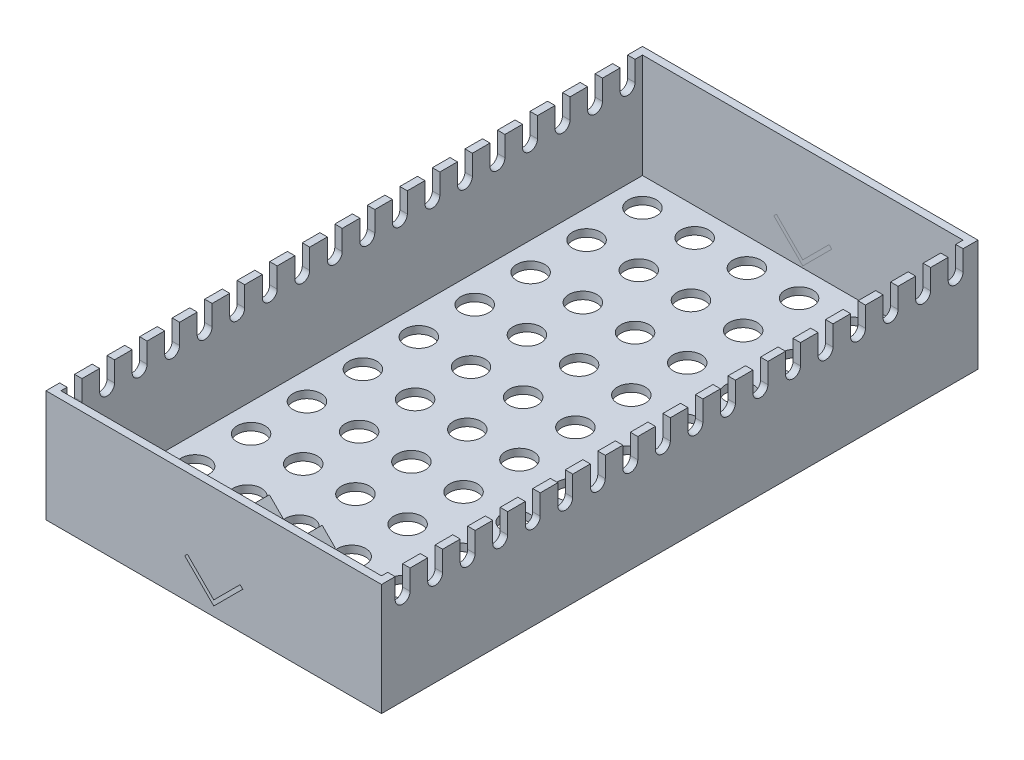
SolidWorks part; units mm, degrees
ref_plane "Front Plane" through (0, 0, 0) normal (0, 0, 1) x (1, 0, 0)
ref_plane "Top Plane" through (0, 0, 0) normal (0, 1, 0) x (1, 0, 0)
ref_plane "Right Plane" through (0, 0, 0) normal (1, 0, 0) x (0, 0, -1)
sketch "Sketch1" plane through (0, 0, 0) normal (0, 0, 1) x (1, 0, 0)
  line L0 (0, 4.9711) -> (-8.9803, 13.9513)
  line L1 (-57.15, 0) -> (57.15, 0)
  line L2 (-57.15, 0) -> (-57.15, 38.1)
  line L3 (-57.15, 38.1) -> (57.15, 38.1)
  line L4 (57.15, 0) -> (57.15, 38.1)
  line L5 (-8.9803, 13.9513) -> (-9.8783, 13.0533)
  line L6 (-9.8783, 13.0533) -> (0, 3.175)
  line L7 (0, 3.175) -> (9.8783, 13.0533)
  line L8 (9.8783, 13.0533) -> (8.9803, 13.9513)
  line L9 (8.9803, 13.9513) -> (0, 4.9711)
  point P10 (0, 0)
  point P12 (0, 0)
  point P13 (0, 0)
  point P14 (9.8783, 13.0533)
  point P15 (0, 0)
  dimension "D1" = 12.7
  dimension "D2" = 1.27
  dimension "D3" = 3.175
  dimension "D4" = 45
  dimension "D5" = 114.3
  dimension "D6" = 38.1
extrude "Boss-Extrude1" add sketch "Sketch1" against normal blind 203.2
shell "Shell1" thickness 2.54
sketch "Sketch3" plane through (0, 0, 0) normal (1, 0, 0) x (0, 0, -1)
  line L0 (203.2, 38.1) -> (0, 38.1) construction
  line L1 (200.66, 38.1) -> (27.94, 38.1)
  line L2 (200.66, 38.1) -> (200.66, 2.54)
  line L3 (200.66, 2.54) -> (27.94, 2.54)
  line L4 (27.94, 38.1) -> (27.94, 2.54)
  line L5 (203.2, 0) -> (0, 0) construction
  line L6 (0, 0) -> (0, 38.1) construction
  line L7 (203.2, 0) -> (203.2, 38.1) construction
  dimension "D1" = 2.54
  dimension "D2" = 27.94
  dimension "D3" = 2.54
extrude "Cut-Extrude1" cut sketch "Sketch3" against normal up to next and the other way up to next
sketch "Sketch4" plane through (0, 0, -27.94) normal (0, 0, -1) x (-1, 0, 0)
  line L5 (-9.8783, 13.0533) -> (-8.9803, 13.9513)
  line L6 (-8.9803, 13.9513) -> (0, 4.9711)
  line L7 (0, 4.9711) -> (8.9803, 13.9513)
  line L8 (8.9803, 13.9513) -> (9.8783, 13.0533)
  line L9 (9.8783, 13.0533) -> (0, 3.175)
  line L10 (0, 3.175) -> (-9.8783, 13.0533)
extrude "Boss-Extrude2" add sketch "Sketch4" against normal blind 2.54
sketch "Sketch5" plane through (-57.15, 0, 0) normal (-1, 0, 0) x (0, 0, 1)
  line L0 (-203.2, 38.1) -> (0, 38.1) construction
  line L1 (-198.12, 38.1) -> (-193.04, 38.1)
  line L2 (-198.12, 38.1) -> (-198.12, 31.242)
  line L4 (-193.04, 38.1) -> (-193.04, 31.242)
  line L5 (-203.2, 38.1) -> (-203.2, 0) construction
  line L6 (-181.958, 38.1) -> (-181.958, 31.242)
  line L7 (-187.038, 38.1) -> (-181.958, 38.1)
  line L8 (-187.038, 38.1) -> (-187.038, 31.242)
  line L9 (-170.876, 38.1) -> (-170.876, 31.242)
  line L10 (-175.956, 38.1) -> (-170.876, 38.1)
  line L11 (-175.956, 38.1) -> (-175.956, 31.242)
  line L12 (-159.794, 38.1) -> (-159.794, 31.242)
  line L13 (-164.874, 38.1) -> (-159.794, 38.1)
  line L14 (-164.874, 38.1) -> (-164.874, 31.242)
  line L15 (-148.7119, 38.1) -> (-148.7119, 31.242)
  line L16 (-153.7919, 38.1) -> (-148.7119, 38.1)
  line L17 (-153.7919, 38.1) -> (-153.7919, 31.242)
  line L18 (-137.6299, 38.1) -> (-137.6299, 31.242)
  line L19 (-142.7099, 38.1) -> (-137.6299, 38.1)
  line L20 (-142.7099, 38.1) -> (-142.7099, 31.242)
  line L21 (-126.5479, 38.1) -> (-126.5479, 31.242)
  line L22 (-131.6279, 38.1) -> (-126.5479, 38.1)
  line L23 (-131.6279, 38.1) -> (-131.6279, 31.242)
  line L24 (-115.4659, 38.1) -> (-115.4659, 31.242)
  line L25 (-120.5459, 38.1) -> (-115.4659, 38.1)
  line L26 (-120.5459, 38.1) -> (-120.5459, 31.242)
  line L27 (-104.3839, 38.1) -> (-104.3839, 31.242)
  line L28 (-109.4639, 38.1) -> (-104.3839, 38.1)
  line L29 (-109.4639, 38.1) -> (-109.4639, 31.242)
  line L30 (-93.3019, 38.1) -> (-93.3019, 31.242)
  line L31 (-98.3819, 38.1) -> (-93.3019, 38.1)
  line L32 (-98.3819, 38.1) -> (-98.3819, 31.242)
  line L33 (-82.2199, 38.1) -> (-82.2199, 31.242)
  line L34 (-87.2999, 38.1) -> (-82.2199, 38.1)
  line L35 (-87.2999, 38.1) -> (-87.2999, 31.242)
  line L36 (-71.1378, 38.1) -> (-71.1378, 31.242)
  line L37 (-76.2178, 38.1) -> (-71.1378, 38.1)
  line L38 (-76.2178, 38.1) -> (-76.2178, 31.242)
  line L39 (-60.0558, 38.1) -> (-60.0558, 31.242)
  line L40 (-65.1358, 38.1) -> (-60.0558, 38.1)
  line L41 (-65.1358, 38.1) -> (-65.1358, 31.242)
  line L42 (-48.9738, 38.1) -> (-48.9738, 31.242)
  line L43 (-54.0538, 38.1) -> (-48.9738, 38.1)
  line L44 (-54.0538, 38.1) -> (-54.0538, 31.242)
  line L45 (-37.8918, 38.1) -> (-37.8918, 31.242)
  line L46 (-42.9718, 38.1) -> (-37.8918, 38.1)
  line L47 (-42.9718, 38.1) -> (-42.9718, 31.242)
  line L48 (-26.8098, 38.1) -> (-26.8098, 31.242)
  line L49 (-31.8898, 38.1) -> (-26.8098, 38.1)
  line L50 (-31.8898, 38.1) -> (-31.8898, 31.242)
  line L51 (-15.7278, 38.1) -> (-15.7278, 31.242)
  line L52 (-20.8078, 38.1) -> (-15.7278, 38.1)
  line L53 (-20.8078, 38.1) -> (-20.8078, 31.242)
  line L54 (-4.6458, 38.1) -> (-4.6458, 31.242)
  line L55 (-9.7258, 38.1) -> (-4.6458, 38.1)
  line L56 (-9.7258, 38.1) -> (-9.7258, 31.242)
  arc A0 (-198.12, 31.242) -> (-193.04, 31.242) centre (-195.58, 31.242) ccw
  arc A1 (-187.038, 31.242) -> (-181.958, 31.242) centre (-184.498, 31.242) ccw
  arc A2 (-175.956, 31.242) -> (-170.876, 31.242) centre (-173.416, 31.242) ccw
  arc A3 (-164.874, 31.242) -> (-159.794, 31.242) centre (-162.334, 31.242) ccw
  arc A4 (-153.7919, 31.242) -> (-148.7119, 31.242) centre (-151.2519, 31.242) ccw
  arc A5 (-142.7099, 31.242) -> (-137.6299, 31.242) centre (-140.1699, 31.242) ccw
  arc A6 (-131.6279, 31.242) -> (-126.5479, 31.242) centre (-129.0879, 31.242) ccw
  arc A7 (-120.5459, 31.242) -> (-115.4659, 31.242) centre (-118.0059, 31.242) ccw
  arc A8 (-109.4639, 31.242) -> (-104.3839, 31.242) centre (-106.9239, 31.242) ccw
  arc A9 (-98.3819, 31.242) -> (-93.3019, 31.242) centre (-95.8419, 31.242) ccw
  arc A10 (-87.2999, 31.242) -> (-82.2199, 31.242) centre (-84.7599, 31.242) ccw
  arc A11 (-76.2178, 31.242) -> (-71.1378, 31.242) centre (-73.6778, 31.242) ccw
  arc A12 (-65.1358, 31.242) -> (-60.0558, 31.242) centre (-62.5958, 31.242) ccw
  arc A13 (-54.0538, 31.242) -> (-48.9738, 31.242) centre (-51.5138, 31.242) ccw
  arc A14 (-42.9718, 31.242) -> (-37.8918, 31.242) centre (-40.4318, 31.242) ccw
  arc A15 (-31.8898, 31.242) -> (-26.8098, 31.242) centre (-29.3498, 31.242) ccw
  arc A16 (-20.8078, 31.242) -> (-15.7278, 31.242) centre (-18.2678, 31.242) ccw
  arc A17 (-9.7258, 31.242) -> (-4.6458, 31.242) centre (-7.1858, 31.242) ccw
  point P9 (-195.58, 28.702)
  dimension "D1" = 5.08
  dimension "D2" = 5.08
  dimension "D3" = 9.398
  dimension "D4" = 18
extrude "Cut-Extrude2" cut sketch "Sketch5" against normal through all both and the other way through all
sketch "Sketch6" plane through (0, 2.54, 0) normal (0, 1, 0) x (1, 0, 0)
  line L0 (54.61, 200.66) -> (-54.61, 200.66) construction
  line L1 (-54.61, 200.66) -> (-54.61, 2.54) construction
  circle A0 centre (-45.085, 191.135) radius 4.7625
  circle A1 centre (-27.305, 191.135) radius 4.7625
  circle A2 centre (-9.525, 191.135) radius 4.7625
  circle A3 centre (8.255, 191.135) radius 4.7625
  circle A4 centre (26.035, 191.135) radius 4.7625
  circle A5 centre (43.815, 191.135) radius 4.7625
  circle A6 centre (-27.305, 172.085) radius 4.7625
  circle A7 centre (-9.525, 172.085) radius 4.7625
  circle A8 centre (8.255, 172.085) radius 4.7625
  circle A9 centre (26.035, 172.085) radius 4.7625
  circle A10 centre (43.815, 172.085) radius 4.7625
  circle A11 centre (-27.305, 153.035) radius 4.7625
  circle A12 centre (-9.525, 153.035) radius 4.7625
  circle A13 centre (8.255, 153.035) radius 4.7625
  circle A14 centre (26.035, 153.035) radius 4.7625
  circle A15 centre (43.815, 153.035) radius 4.7625
  circle A16 centre (-27.305, 133.985) radius 4.7625
  circle A17 centre (-9.525, 133.985) radius 4.7625
  circle A18 centre (8.255, 133.985) radius 4.7625
  circle A19 centre (26.035, 133.985) radius 4.7625
  circle A20 centre (43.815, 133.985) radius 4.7625
  circle A21 centre (-27.305, 114.935) radius 4.7625
  circle A22 centre (-9.525, 114.935) radius 4.7625
  circle A23 centre (8.255, 114.935) radius 4.7625
  circle A24 centre (26.035, 114.935) radius 4.7625
  circle A25 centre (43.815, 114.935) radius 4.7625
  circle A26 centre (-27.305, 95.885) radius 4.7625
  circle A27 centre (-9.525, 95.885) radius 4.7625
  circle A28 centre (8.255, 95.885) radius 4.7625
  circle A29 centre (26.035, 95.885) radius 4.7625
  circle A30 centre (43.815, 95.885) radius 4.7625
  circle A31 centre (-27.305, 76.835) radius 4.7625
  circle A32 centre (-9.525, 76.835) radius 4.7625
  circle A33 centre (8.255, 76.835) radius 4.7625
  circle A34 centre (26.035, 76.835) radius 4.7625
  circle A35 centre (43.815, 76.835) radius 4.7625
  circle A36 centre (-27.305, 57.785) radius 4.7625
  circle A37 centre (-9.525, 57.785) radius 4.7625
  circle A38 centre (8.255, 57.785) radius 4.7625
  circle A39 centre (26.035, 57.785) radius 4.7625
  circle A40 centre (43.815, 57.785) radius 4.7625
  circle A41 centre (-27.305, 38.735) radius 4.7625
  circle A42 centre (-9.525, 38.735) radius 4.7625
  circle A43 centre (8.255, 38.735) radius 4.7625
  circle A44 centre (26.035, 38.735) radius 4.7625
  circle A45 centre (43.815, 38.735) radius 4.7625
  circle A46 centre (-45.085, 172.085) radius 4.7625
  circle A47 centre (-45.085, 153.035) radius 4.7625
  circle A48 centre (-45.085, 133.985) radius 4.7625
  circle A49 centre (-45.085, 114.935) radius 4.7625
  circle A50 centre (-45.085, 95.885) radius 4.7625
  circle A51 centre (-45.085, 76.835) radius 4.7625
  circle A52 centre (-45.085, 57.785) radius 4.7625
  circle A53 centre (-45.085, 38.735) radius 4.7625
  dimension "D3" = 9.525
  dimension "D1" = 9.525
  dimension "D2" = 9.525
  dimension "D4" = 6
  dimension "D5" = 9
extrude "Cut-Extrude3" cut sketch "Sketch6" against normal through all both and the other way through all
fillet "Fillet1" radius 2.54 3 edges at (0, 8.5632, -15.24) (2.9571, 2.54, -15.24) (-2.9571, 2.54, -15.24)
sketch "Sketch7" plane through (0, 0, -203.2) normal (0, 0, -1) x (-1, 0, 0)
  line L0 (-8.9803, 13.9513) -> (-9.8783, 13.0533)
  line L1 (-9.8783, 13.0533) -> (0, 3.175)
  line L2 (0, 3.175) -> (9.8783, 13.0533)
  line L3 (8.9803, 13.9513) -> (0, 4.9711)
  line L4 (0, 4.9711) -> (-8.9803, 13.9513)
  line L5 (8.9803, 13.9513) -> (9.8783, 13.0533)
extrude "Boss-Extrude3" add sketch "Sketch7" against normal blind 2.54 separate body
